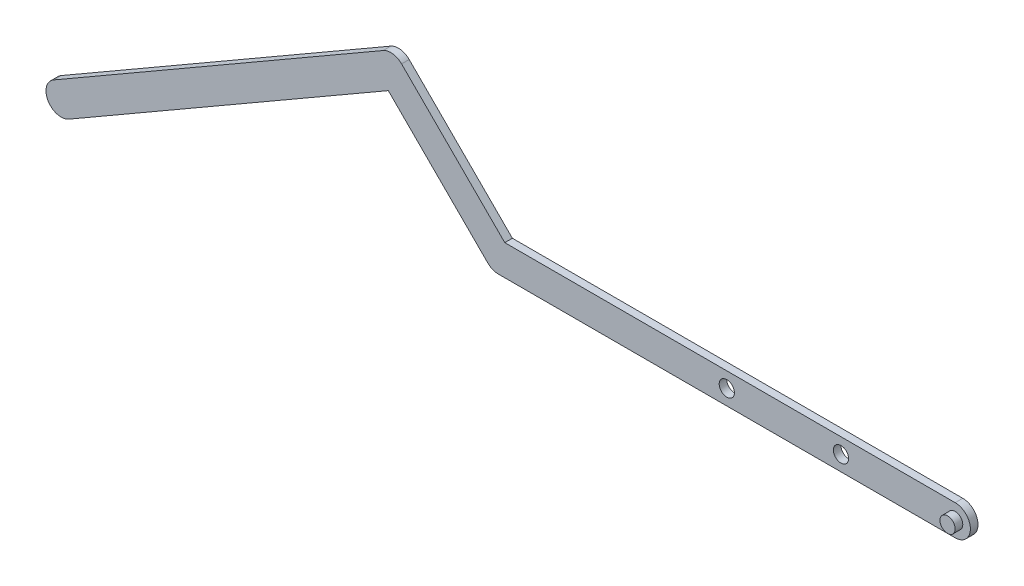
SolidWorks part; units mm, degrees
ref_plane "前视基准面" through (0, 0, 0) normal (0, 0, 1) x (1, 0, 0)
ref_plane "上视基准面" through (0, 0, 0) normal (0, 1, 0) x (1, 0, 0)
ref_plane "右视基准面" through (0, 0, 0) normal (1, 0, 0) x (0, 0, -1)
sketch "草图1" plane through (0, 0, 0) normal (0, 0, 1) x (1, 0, 0)
  line L0 (0, 2) -> (30, 2)
  line L1 (0, -2) -> (30, -2)
  line L2 (30, 2) -> (30, -2) construction
  line L3 (0, 0) -> (30, 0) construction
  line L4 (0, 2) -> (-29.1716, 2)
  line L6 (-30, 2) -> (-30, -2) construction
  line L7 (0, -2) -> (-30, -2)
  line L10 (-30, 0) -> (-44.1421, 14.1421) construction
  line L11 (-44.1421, 14.1421) -> (-87.4434, -10.8579) construction
  line L12 (-42.7279, 15.5563) -> (-29.1716, 2)
  line L13 (-44.4712, 11.6428) -> (-31.4142, -1.4142)
  line L14 (-44.4712, 11.6428) -> (-86.4434, -12.5899)
  line L15 (-88.4434, -9.1258) -> (-45.1421, 15.8742)
  arc A1 (30, -2) -> (30, 2) centre (30, 0) ccw
  circle A2 centre (15, 0) radius 1
  circle A3 centre (0, 0) radius 1
  arc A8 (-88.4434, -9.1258) -> (-86.4434, -12.5899) centre (-87.4434, -10.8579) ccw
  arc A9 (-31.4142, -1.4142) -> (-30, -2) centre (-30, 0) ccw
  arc A11 (-42.7279, 15.5563) -> (-45.1421, 15.8742) centre (-44.1421, 14.1421) ccw
  dimension "D1" = 20
  dimension "D4" = 2
  dimension "D5" = 2
  dimension "D7" = 50
  dimension "D9" = 4
  dimension "D2" = 30
  dimension "D3" = 30
  dimension "D6" = 30
extrude "凸台-拉伸1" add sketch "草图1" along normal blind 1
sketch "草图2" plane through (0, 0, 1) normal (0, 0, 1) x (1, 0, 0)
  circle A0 centre (30, 0) radius 1
  dimension "D1" = 2
extrude "凸台-拉伸2" add sketch "草图2" along normal blind 1
